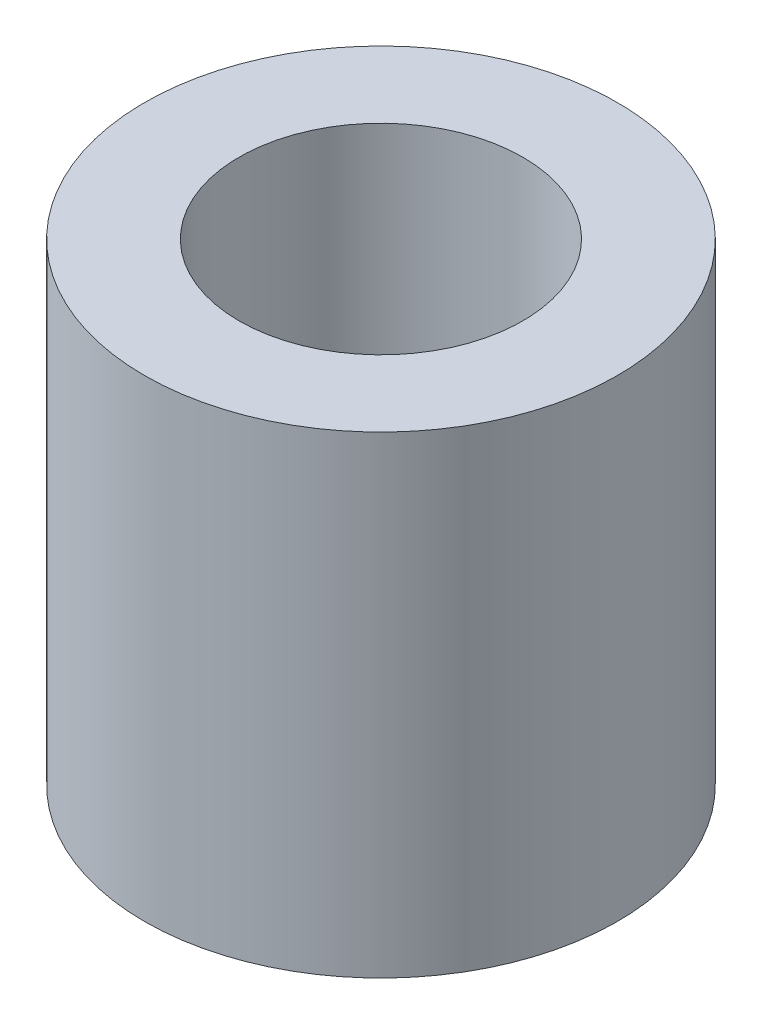
SolidWorks part; units mm, degrees
ref_plane "前视基准面" through (0, 0, 0) normal (0, 0, 1) x (1, 0, 0)
ref_plane "上视基准面" through (0, 0, 0) normal (0, 1, 0) x (1, 0, 0)
ref_plane "右视基准面" through (0, 0, 0) normal (1, 0, 0) x (0, 0, -1)
sketch "草图1" plane through (0, 0, 0) normal (0, 1, 0) x (1, 0, 0)
  circle A0 centre (0, 0) radius 1.5
  circle A1 centre (0, 0) radius 2.5
  dimension "D1" = 3
  dimension "D2" = 5
extrude "凸台-拉伸1" add sketch "草图1" along normal blind 5
